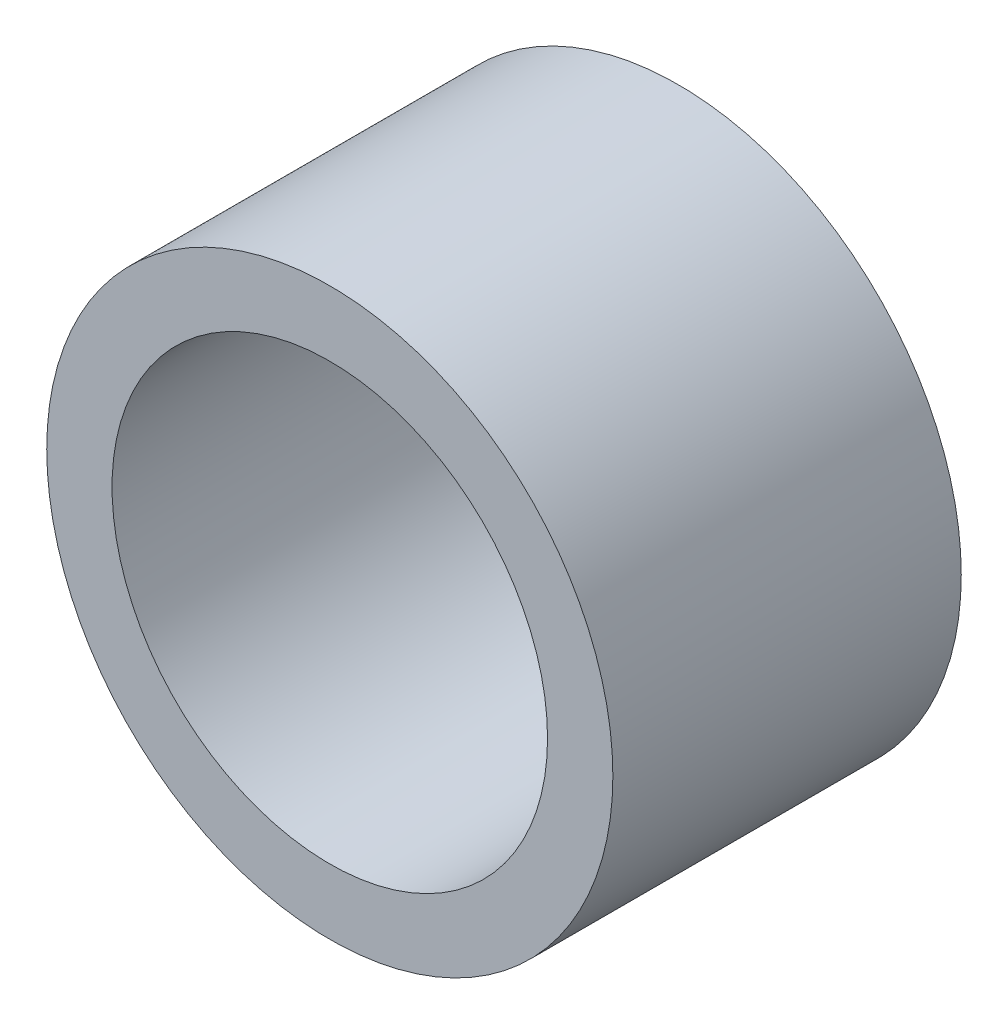
SolidWorks part; units mm, degrees
material "Alloy Steel"
ref_plane "Front Plane" through (0, 0, 0) normal (0, 0, 1) x (1, 0, 0)
ref_plane "Top Plane" through (0, 0, 0) normal (0, 1, 0) x (1, 0, 0)
ref_plane "Right Plane" through (0, 0, 0) normal (1, 0, 0) x (0, 0, -1)
sketch "Sketch1" plane through (0, 0, 0) normal (0, 0, 1) x (1, 0, 0)
  circle A0 centre (0, 0) radius 7.9375
  circle A1 centre (0, 0) radius 10.3188
  dimension "D1" = 15.875
  dimension "D2" = 20.6375
extrude "Boss-Extrude1" add sketch "Sketch1" along normal blind 12.7
